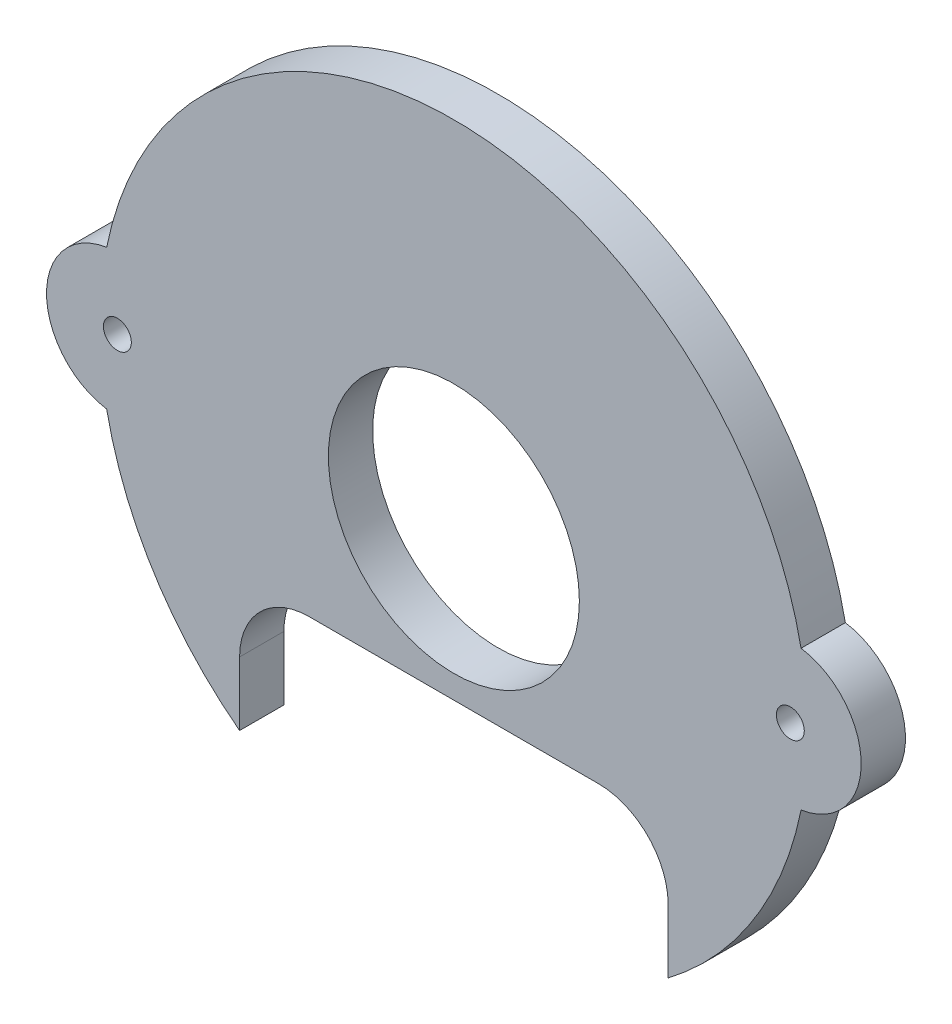
SolidWorks part; units mm, degrees
ref_plane "Front" through (0, 0, 0) normal (0, 0, 1) x (1, 0, 0)
ref_plane "Top" through (0, 0, 0) normal (0, 1, 0) x (1, 0, 0)
ref_plane "Right" through (0, 0, 0) normal (1, 0, 0) x (0, 0, -1)
sketch "Sketch1" plane through (0, 0, 0) normal (0, 0, 1) x (1, 0, 0)
  circle A11 centre (-24.13, 0) radius 1 construction
  circle A12 centre (24.13, 0) radius 1 construction
  arc A13 (24.8987, -5.0215) -> (24.8987, 5.0215) centre (24.13, 0) ccw construction
  arc A14 (-24.8987, -5.0215) -> (24.8987, -5.0215) centre (0, 0) ccw construction
  arc A15 (-24.8987, 5.0215) -> (-24.8987, -5.0215) centre (-24.13, 0) ccw construction
  arc A16 (24.8987, 5.0215) -> (-24.8987, 5.0215) centre (0, 0) ccw construction
  circle A17 centre (-24.13, 0) radius 1
  circle A18 centre (24.13, 0) radius 1
  arc A19 (24.8987, -5.0215) -> (24.8987, 5.0215) centre (24.13, 0) ccw
  arc A20 (-24.8987, -5.0215) -> (24.8987, -5.0215) centre (0, 0) ccw
  arc A21 (-24.8987, 5.0215) -> (-24.8987, -5.0215) centre (-24.13, 0) ccw
  arc A22 (24.8987, 5.0215) -> (-24.8987, 5.0215) centre (0, 0) ccw
  circle A23 centre (0, 0) radius 9
extrude "Boss-Extrude1" add sketch "Sketch1" along normal blind 3.175
sketch "Sketch2" plane through (0, 0, 0) normal (0, 0, 1) x (1, 0, 0)
  line L0 (-15.367, -20.2241) -> (-15.367, -10.6545)
  line L8 (-15.367, -10.6545) -> (15.367, -10.6545)
  line L13 (15.367, -10.6545) -> (15.367, -20.2241)
  arc A4 (-24.8987, -5.0215) -> (24.8987, -5.0215) centre (0, 0) ccw construction
  arc A5 (-15.367, -20.2241) -> (15.367, -20.2241) centre (0, 0) ccw
  point P5 (0, 0)
  dimension "D1" = 9.5696
extrude "Cut-Extrude3" cut sketch "Sketch2" along normal blind 9.398
fillet "Fillet3" radius 5 2 edges at (15.367, -10.6545, 1.5875) (-15.367, -10.6545, 1.5875)
